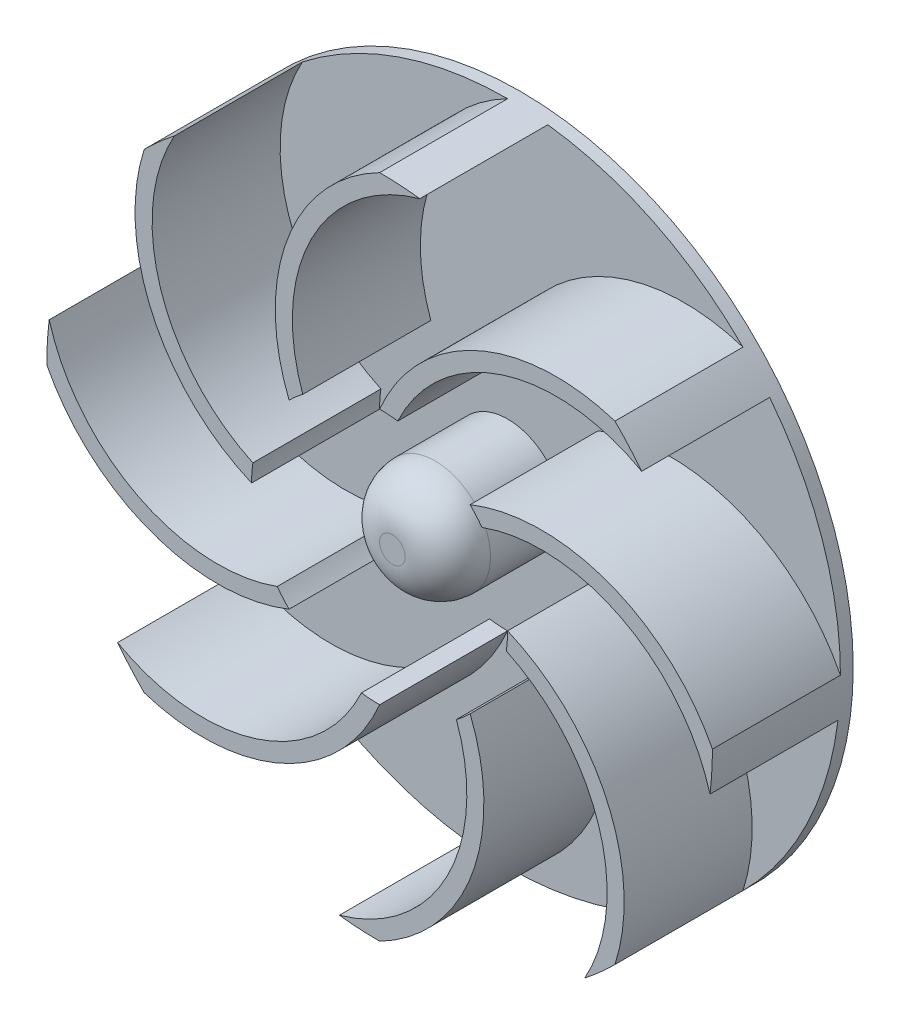
SolidWorks part; units mm, degrees
ref_plane "Front Plane" through (0, 0, 0) normal (0, 0, 1) x (1, 0, 0)
ref_plane "Top Plane" through (0, 0, 0) normal (0, 1, 0) x (1, 0, 0)
ref_plane "Right Plane" through (0, 0, 0) normal (1, 0, 0) x (0, 0, -1)
sketch "Sketch1" plane through (0, 0, 0) normal (1, 0, 0) x (0, 0, -1)
  line L0 (0, 0) -> (0, 78)
  line L1 (0, 78) -> (-3, 78)
  line L2 (-3, 78) -> (-3, 13)
  line L3 (-3, 13) -> (-20, 13)
  line L4 (-30, 3) -> (-30, 0)
  line L5 (-30, 0) -> (0, 0)
  arc A0 (-20, 13) -> (-30, 3) centre (-20, 3) ccw
  point P9 (-30, 13)
  dimension "D5" = 10
  dimension "D1" = 3
  dimension "D2" = 78
  dimension "D3" = 30
  dimension "D4" = 13
revolve "Revolve1" add sketch "Sketch1" angle 360 about L5
sketch "Sketch2" plane through (0, 0, 3) normal (0, 0, 1) x (1, 0, 0)
  line L0 (0, 0) -> (0, 78) construction
  line L1 (0, 0) -> (-21.2132, 21.2132) construction
  arc A0 (-17.9968, 24.0024) -> (-21.2132, 21.2132) centre (0, 0) ccw
  circle A1 centre (0, 0) radius 78 construction
  arc A2 (0, 78) -> (-21.2132, 21.2132) centre (20.5517, 37.9672) ccw
  arc A3 (9.425, 77.4285) -> (-17.9968, 24.0024) centre (20.5517, 37.9672) ccw
  circle A4 centre (0, 0) radius 78
  arc A6 (1.8268, 74.4415) -> (-17.5008, 22.7024) centre (20.5517, 37.9672) ccw construction
  circle M4 centre (0, 0) radius 78
  dimension "D1" = 60
  dimension "D3" = 45
  dimension "D2" = 45
  dimension "D4" = 4
extrude "Boss-Extrude1" add sketch "Sketch2" along normal blind 30 contours A3 A2 A0 M4
pattern_circular "CirPattern1" count 8 over 360 about axis through (0, 0, 0) along (0, 0, 1) of "Boss-Extrude1"
sketch "Sketch3" plane through (0, 0, 0) normal (0, 0, -1) x (-1, 0, 0)
  circle A0 centre (0, 0) radius 8
  dimension "D1" = 16
extrude "Boss-Extrude2" add sketch "Sketch3" along normal blind 30
